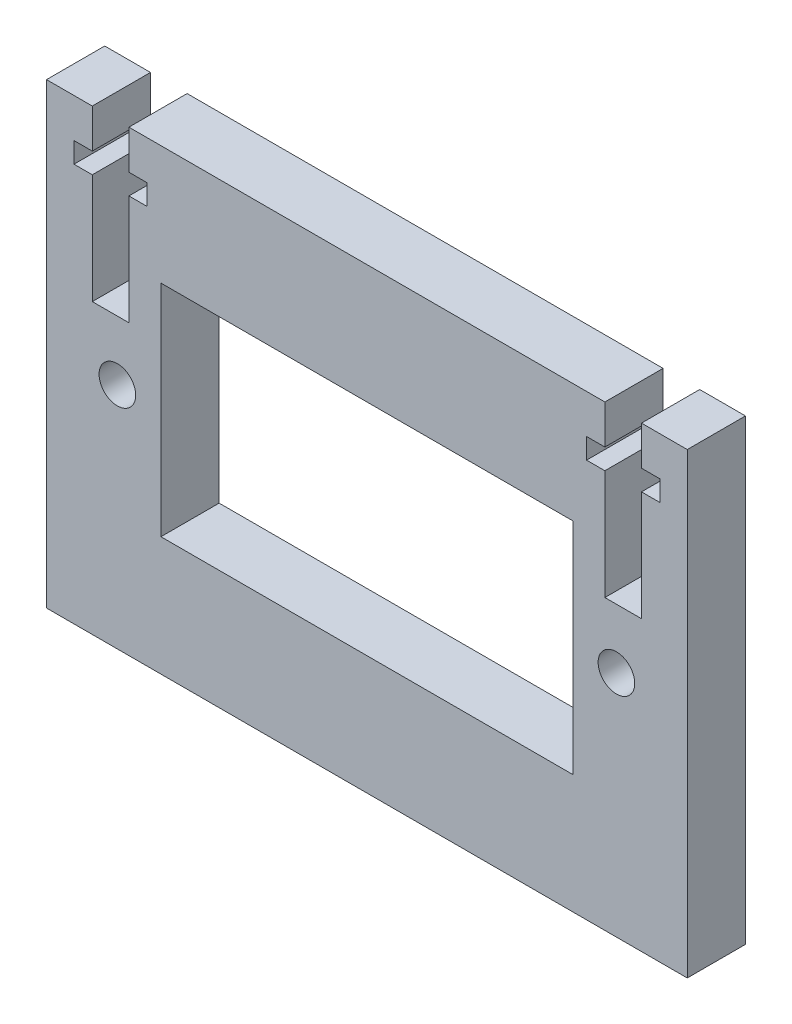
SolidWorks part; units mm, degrees
ref_plane "Front Plane" through (0, 0, 0) normal (0, 0, 1) x (1, 0, 0)
ref_plane "Top Plane" through (0, 0, 0) normal (0, 1, 0) x (1, 0, 0)
ref_plane "Right Plane" through (0, 0, 0) normal (1, 0, 0) x (0, 0, -1)
sketch "Sketch1" plane through (0, 0, 0) normal (0, 0, 1) x (1, 0, 0)
  line L1 (17.5, 12.5) -> (-17.5, 12.5)
  line L2 (17.5, 12.5) -> (17.5, -12.5)
  line L3 (17.5, -12.5) -> (-17.5, -12.5)
  line L4 (-17.5, 12.5) -> (-17.5, -12.5)
  line L5 (17.5, 12.5) -> (-17.5, -12.5) construction
  line L6 (17.5, -12.5) -> (-17.5, 12.5) construction
  point P0 (0, 0)
  dimension "D1" = 35
  dimension "D2" = 25
extrude "Boss-Extrude1" add sketch "Sketch1" along normal blind 3.18
sketch "Sketch2" plane through (0, 0, 3.18) normal (0, 0, 1) x (1, 0, 0)
  line L1 (11.25, 6) -> (-11.25, 6)
  line L2 (11.25, 6) -> (11.25, -6)
  line L3 (11.25, -6) -> (-11.25, -6)
  line L4 (-11.25, 6) -> (-11.25, -6)
  line L5 (11.25, 6) -> (-11.25, -6) construction
  line L6 (11.25, -6) -> (-11.25, 6) construction
  point P0 (0, 0)
  dimension "D1" = 22.5
  dimension "D2" = 12
extrude "Cut-Extrude1" cut sketch "Sketch2" against normal blind 3.18
sketch "Sketch3" plane through (0, 0, 3.18) normal (0, 0, 1) x (1, 0, 0)
  line L0 (-11.25, 6) -> (-11.25, -6) construction
  circle A0 centre (-13.63, 0) radius 1
  dimension "D1" = 2
  dimension "D2" = 2.38
extrude "Cut-Extrude2" cut sketch "Sketch3" against normal blind 3.18
mirror "Mirror1" about plane through (0, 0, 0) normal (1, 0, 0) of "Cut-Extrude2"
sketch "Sketch5" plane through (0, 0, 3.18) normal (0, 0, 1) x (1, 0, 0)
  line L0 (17.5, 12.5) -> (-17.5, 12.5) construction
  line L1 (-13, 12.5) -> (-15, 12.5)
  line L2 (-13, 12.5) -> (-13, 10.368)
  line L3 (-13, 3.248) -> (-15, 3.248)
  line L4 (-15, 12.5) -> (-15, 10.368)
  line L5 (-13, 12.5) -> (-15, 3.248) construction
  line L6 (-13, 3.248) -> (-15, 12.5) construction
  line L7 (-16, 10.368) -> (-15, 10.368)
  line L8 (-16, 10.368) -> (-16, 9.248)
  line L9 (-16, 9.248) -> (-15, 9.248)
  line L10 (-12, 10.368) -> (-12, 9.248)
  line L11 (-16, 10.368) -> (-12, 9.248) construction
  line L12 (-16, 9.248) -> (-12, 10.368) construction
  line L13 (-14, 12.5) -> (-14, 3.248) construction
  line L14 (-17.5, 12.5) -> (-17.5, -12.5) construction
  line L15 (-13, 10.368) -> (-12, 10.368)
  line L16 (-13, 9.248) -> (-13, 3.248)
  line L17 (-13, 9.248) -> (-12, 9.248)
  line L18 (-15, 9.248) -> (-15, 3.248)
  point P0 (-14, 7.874)
  point P5 (-14, 9.808)
  dimension "D1" = 2
  dimension "D2" = 4
  dimension "D3" = 1.12
  dimension "D4" = 9.252
  dimension "D5" = 6
  dimension "D6" = 2.5
extrude "Cut-Extrude4" cut sketch "Sketch5" against normal blind 3.18
mirror "Mirror2" about plane through (0, 0, 0) normal (1, 0, 0) of "Cut-Extrude4"
